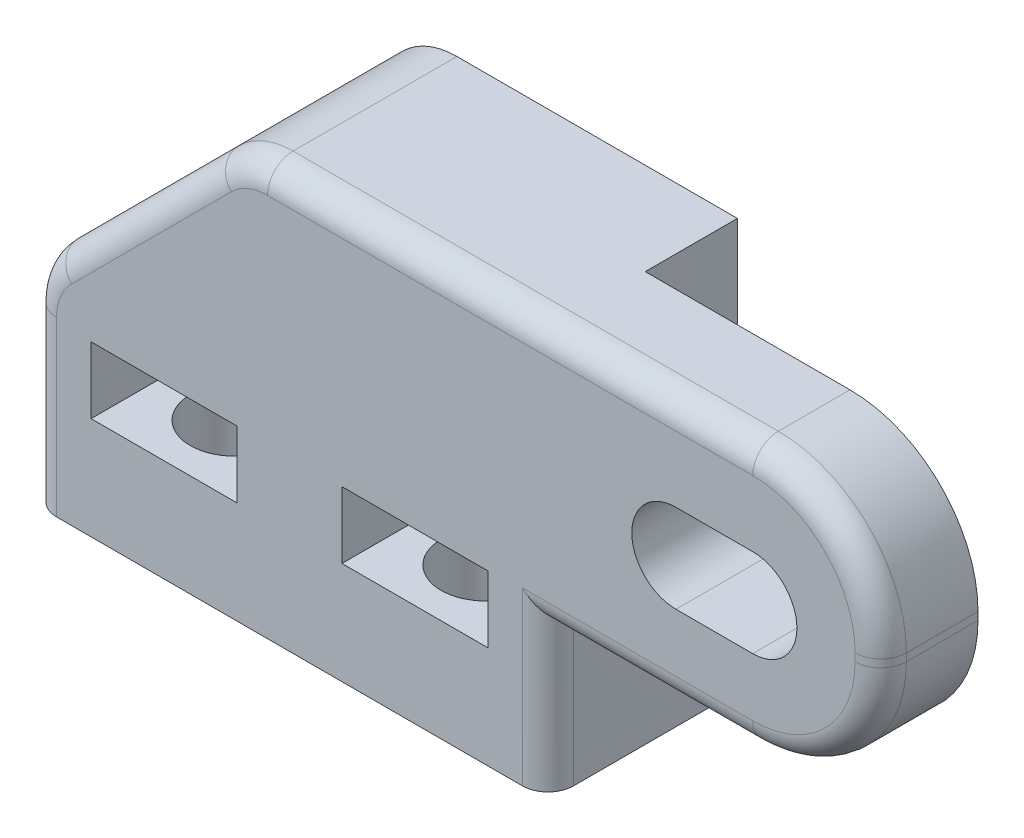
SolidWorks part; units mm, degrees
material "ABS"
ref_plane "Front Plane" through (0, 0, 0) normal (0, 0, 1) x (1, 0, 0)
ref_plane "Top Plane" through (0, 0, 0) normal (0, 1, 0) x (1, 0, 0)
ref_plane "Right Plane" through (0, 0, 0) normal (1, 0, 0) x (0, 0, -1)
sketch "Sketch1" plane through (0, 0, 0) normal (0, 0, 1) x (1, 0, 0)
  line L0 (0, 0) -> (20.2, 0)
  line L1 (20.2, 0) -> (20.2, 5.7)
  line L2 (20.2, 5.7) -> (33.2, 5.7)
  line L3 (33.2, 5.7) -> (33.2, 16)
  line L4 (33.2, 16) -> (0, 16)
  line L5 (0, 16) -> (0, 0)
  line L6 (25.2, 16) -> (25.2, 5.7) construction
  line L7 (25.2, 12.425) -> (28.2, 12.425)
  line L8 (25.2, 8.975) -> (28.2, 8.975)
  arc A0 (25.2, 12.425) -> (25.2, 8.975) centre (25.2, 10.7) ccw
  arc A1 (28.2, 12.425) -> (28.2, 8.975) centre (28.2, 10.7) cw
  dimension "D6" = 3.45
  dimension "D1" = 20.2
  dimension "D2" = 5.7
  dimension "D3" = 5
  dimension "D4" = 5
  dimension "D5" = 16
  dimension "D7" = 8
  dimension "D8" = 3
extrude "Boss-Extrude1" add sketch "Sketch1" along normal blind 7.4
sketch "Sketch2" plane through (33.2, 0, 0) normal (1, 0, 0) x (0, 0, -1)
  line L1 (-3.6, 5.7) -> (0, 5.7)
  line L2 (-3.6, 5.7) -> (-3.6, 16)
  line L3 (-3.6, 16) -> (0, 16)
  line L4 (0, 5.7) -> (0, 16)
  dimension "D1" = 3.6
extrude "Cut-Extrude5" cut sketch "Sketch2" against normal up to surface (13 mm away) up to face at (20.2, 2.85, 3.7)
sketch "Sketch4" plane through (0, 0, 0) normal (0, -1, 0) x (1, 0, 0)
  line L0 (10.1, 0) -> (10.1, 7.4) construction
  line L3 (20.2, 4.65) -> (0, 4.65) construction
  line L5 (0, 7.4) -> (20.2, 7.4) construction
  line L7 (0, 0) -> (20.2, 0) construction
  line L8 (0, 7.4) -> (0, 0) construction
  line L9 (20.2, 7.4) -> (20.2, 0) construction
  circle A0 centre (15, 4.65) radius 1.725
  circle A1 centre (5.2, 4.65) radius 1.725
  dimension "D1" = 3.45
  dimension "D2" = 9.8
  dimension "D3" = 10.1
  dimension "D4" = 2.75
extrude "Cut-Extrude3" cut sketch "Sketch4" against normal blind 9
sketch "Sketch3" plane through (0, 0, 0) normal (0, 0, -1) x (-1, 0, 0)
  line L0 (-15, 9) -> (-15, 0) construction
  line L1 (-17.85, 6.6) -> (-12.15, 6.6)
  line L2 (-17.85, 6.6) -> (-17.85, 4)
  line L3 (-17.85, 4) -> (-12.15, 4)
  line L4 (-12.15, 6.6) -> (-12.15, 4)
  line L5 (-17.85, 6.6) -> (-12.15, 4) construction
  line L6 (-17.85, 4) -> (-12.15, 6.6) construction
  line L7 (-8.05, 6.6) -> (-2.35, 6.6)
  line L8 (-8.05, 6.6) -> (-8.05, 4)
  line L9 (-8.05, 4) -> (-2.35, 4)
  line L10 (-2.35, 6.6) -> (-2.35, 4)
  line L11 (-8.05, 6.6) -> (-2.35, 4) construction
  line L12 (-8.05, 4) -> (-2.35, 6.6) construction
  line L13 (-5.2, 9) -> (-5.2, 0) construction
  point P0 (-15, 5.3)
  point P5 (-5.2, 5.3)
  dimension "D1" = 9.8
  dimension "D2" = 4
  dimension "D3" = 2.6
  dimension "D4" = 5.7
extrude "Cut-Extrude4" cut sketch "Sketch3" against normal through all
chamfer "Chamfer1" distance 8 angle 45 1 edges at (0, 16, 3.7)
fillet "Fillet4" radius 3 2 edges at (8, 16, 3.7) (0, 8, 3.7)
fillet "Fillet5" radius 5 2 edges at (33.2, 5.7, 5.5) (33.2, 16, 5.5)
fillet "Fillet6" radius 1 10 edges at (24.2, 5.7, 7.4) (31.7355, 7.1645, 7.4) (33.2, 10.85, 7.4) (31.7355, 14.5355, 7.4) (18.7213, 16, 7.4) (8.0946, 15.7716, 7.4) (4, 12, 7.4) (20.2, 2.85, 7.4) (0.2284, 7.9054, 7.4) (0, 3.3787, 7.4)
equation "\"D6@Sketch1\"=3.00mm+\"print_free@Parameters@Parameters.SLDPRT\""
equation "\"D1@Sketch4\"=3.00mm+\"print_free@Parameters@Parameters.SLDPRT\""
equation "\"D4@Sketch3\"= 5.50mm+\"print_fit@Parameters@Parameters.SLDPRT\""
equation "\"D3@Sketch3\"=2.40mm+\"print_fit@Parameters@Parameters.SLDPRT\""
equation "\"D8@Sketch1\"=\"LinkADist@Parameters@Parameters.SLDPRT\""
